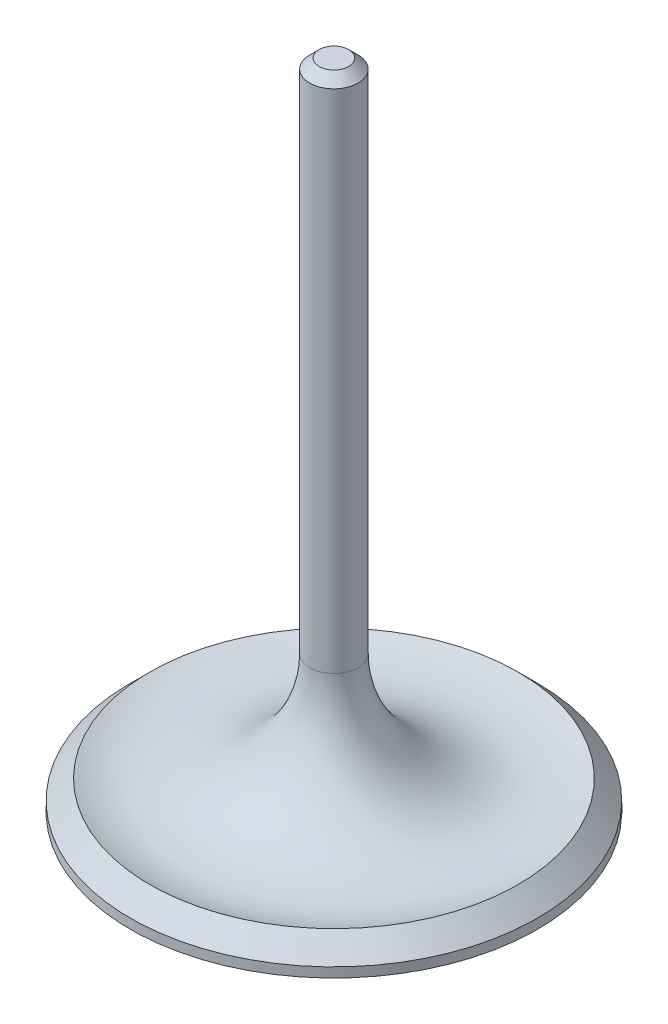
SolidWorks part; units mm, degrees
ref_plane "Front Plane" through (0, 0, 0) normal (0, 0, 1) x (1, 0, 0)
ref_plane "Top Plane" through (0, 0, 0) normal (0, 1, 0) x (1, 0, 0)
ref_plane "Right Plane" through (0, 0, 0) normal (1, 0, 0) x (0, 0, -1)
sketch "Sketch2" plane through (0, 0, 0) normal (1, 0, 0) x (0, 0, -1)
  line L0 (0, 0) -> (0, 85.55)
  line L1 (0, 85.55) -> (3.18, 85.55)
  line L2 (3.18, 85.55) -> (3.18, 17.9547)
  line L3 (24.13, 3.81) -> (26.67, 1.27)
  line L4 (26.67, 1.27) -> (26.67, 0)
  line L5 (26.67, 0) -> (0, 0)
  arc A0 (3.18, 17.9547) -> (24.13, 3.81) centre (18.43, 17.9547) ccw
  dimension "D7" = 15.25
  dimension "D1" = 85.55
  dimension "D2" = 3.18
  dimension "D3" = 26.67
  dimension "D4" = 1.27
  dimension "D5" = 3.81
  dimension "D6" = 45
revolve "Revolve1" add sketch "Sketch2" angle 360 about L0
chamfer "Chamfer1" distance 1.25 angle 45 1 edges at (0, 85.55, -3.18)
